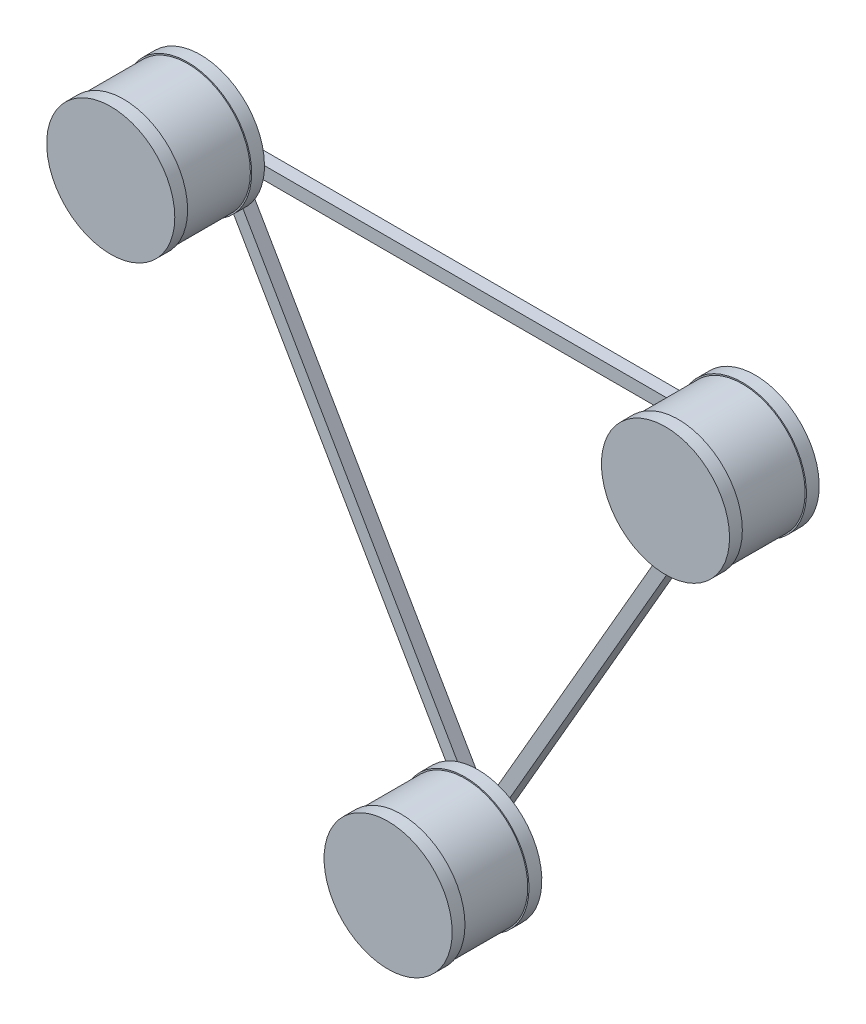
SolidWorks part; units mm, degrees
ref_plane "Front Plane" through (0, 0, 0) normal (0, 0, 1) x (1, 0, 0)
ref_plane "Top Plane" through (0, 0, 0) normal (0, 1, 0) x (1, 0, 0)
ref_plane "Right Plane" through (0, 0, 0) normal (1, 0, 0) x (0, 0, -1)
sketch "Sketch1" plane through (0, 0, 0) normal (0, 0, 1) x (1, 0, 0)
  line L3 (0, -125) -> (-108.2532, 62.5)
  line L4 (-108.2532, 62.5) -> (108.2532, 62.5)
  line L5 (108.2532, 62.5) -> (0, -125)
  line L6 (0, -115) -> (-99.5929, 57.5)
  line L7 (-99.5929, 57.5) -> (99.5929, 57.5)
  line L8 (99.5929, 57.5) -> (0, -115)
  line L9 (-99.5929, 57.5) -> (-108.2532, 62.5) construction
  line L10 (99.5929, 57.5) -> (108.2532, 62.5) construction
  line L11 (0, -115) -> (0, -125) construction
  circle A0 centre (0, 0) radius 125 construction
  point P3 (0, 0)
  point P4 (0, 0)
  point P6 (0, 0)
  point P12 (-123.6042, 59.779)
  point P13 (-107.1341, 33.3939)
  dimension "D1" = 250
  dimension "D2" = 5
  dimension "D3" = 60
  dimension "D4" = 60
  dimension "D5" = 5
extrude "Boss-Extrude1" add sketch "Sketch1" along normal mid plane 5
sketch "Sketch2" plane through (0, 0, 2.5) normal (0, 0, 1) x (1, 0, 0)
  line L0 (-108.2532, 62.5) -> (-99.5929, 57.5) construction
  line L1 (0, 95.8959) -> (0, -38.6565) construction
  line L2 (0, -125) -> (0, -115) construction
  circle A0 centre (-108.2532, 62.5) radius 25
  circle A1 centre (108.2532, 62.5) radius 25
  circle A2 centre (0, -125) radius 25
  point P6 (-103.923, 60)
  point P18 (-103.923, 60)
  point P19 (0, 0)
  point P20 (0, 0)
  point P21 (0, 0)
  point P22 (0, 0)
  point P23 (0, 0)
  dimension "D1" = 50
  dimension "D2" = 50
extrude "Boss-Extrude2" add sketch "Sketch2" along normal blind 5
sketch "Sketch3" plane through (0, 0, 7.5) normal (0, 0, 1) x (1, 0, 0)
  line L0 (0, 28.1093) -> (0, -21.749) construction
  circle A0 centre (-108.2532, 62.5) radius 5
  circle A1 centre (108.2532, 62.5) radius 5
  circle A2 centre (0, -125) radius 5
  dimension "D1" = 10
  dimension "D2" = 10
extrude "Boss-Extrude3" add sketch "Sketch3" along normal blind 25
sketch "Sketch4" plane through (0, 0, 32.5) normal (0, 0, 1) x (1, 0, 0)
  circle A0 centre (0, -125) radius 25
  circle A1 centre (108.2532, 62.5) radius 25
  circle A2 centre (-108.2532, 62.5) radius 25
extrude "Boss-Extrude4" add sketch "Sketch4" along normal blind 5
sketch "Sketch5" plane through (0, 0, 7.5) normal (0, 0, 1) x (1, 0, 0)
  circle A0 centre (-108.2532, 62.5) radius 24.5
  circle A1 centre (-108.2532, 62.5) radius 5.5
  circle A2 centre (108.2532, 62.5) radius 24.5
  circle A3 centre (108.2532, 62.5) radius 5.5
  circle A4 centre (0, -125) radius 24.5
  circle A5 centre (0, -125) radius 5.5
  dimension "D1" = 11
  dimension "D2" = 49
  dimension "D3" = 49
  dimension "D4" = 11
  dimension "D5" = 49
  dimension "D6" = 11
extrude "Boss-Extrude5" add sketch "Sketch5" along normal up to surface (25 mm away) up to face at (-103.2532, 62.5, 32.5)
